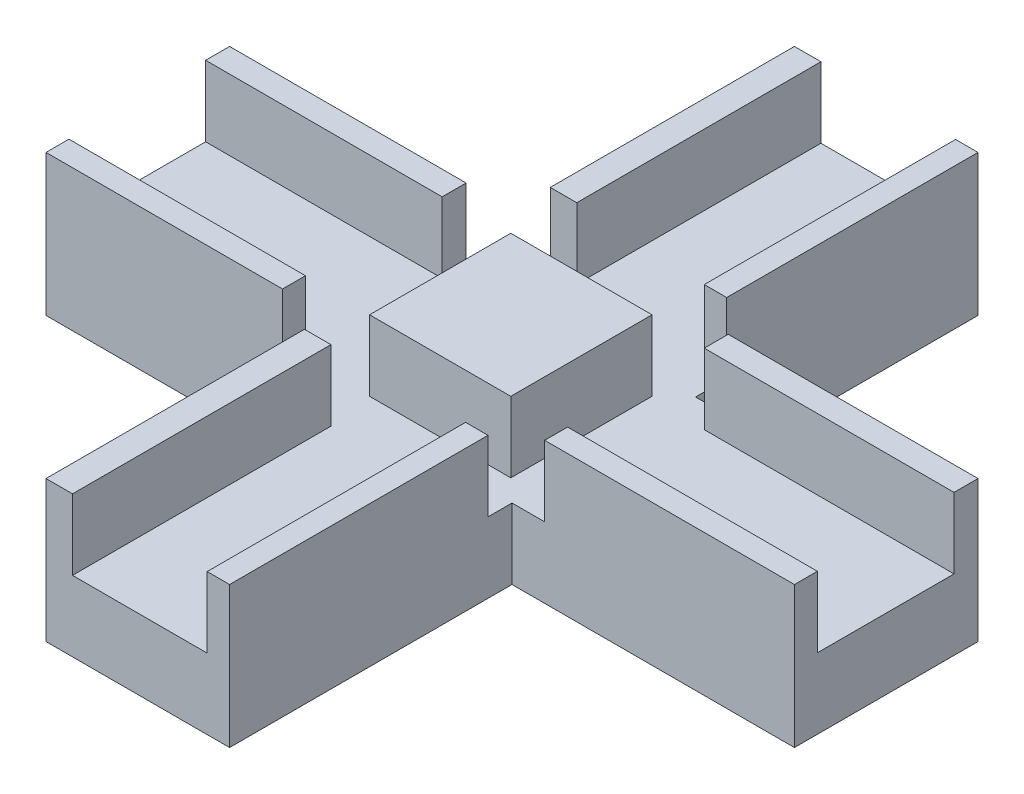
SolidWorks part; units mm, degrees
ref_plane "Front Plane" through (0, 0, 0) normal (0, 0, 1) x (1, 0, 0)
ref_plane "Top Plane" through (0, 0, 0) normal (0, 1, 0) x (1, 0, 0)
ref_plane "Right Plane" through (0, 0, 0) normal (1, 0, 0) x (0, 0, -1)
sketch "Sketch1" plane through (0, 0, 0) normal (0, 1, 0) x (1, 0, 0)
  line L0 (-12.8302, 53) -> (-12.8302, 13)
  line L1 (-12.8302, 13) -> (-52.8302, 13)
  line L2 (-52.8302, 13) -> (-52.8302, -13)
  line L3 (-12.8302, 53) -> (13.1698, 53)
  line L4 (-62.8931, 0) -> (96.6038, 0) construction
  line L5 (0.1698, 63.0629) -> (0.1698, -67) construction
  line L6 (-12.8302, -53) -> (13.1698, -53)
  line L7 (-12.8302, -13) -> (-52.8302, -13)
  line L8 (-12.8302, -53) -> (-12.8302, -13)
  line L9 (13.1698, -53) -> (13.1698, -13)
  line L10 (13.1698, -13) -> (53.1698, -13)
  line L11 (53.1698, 13) -> (53.1698, -13)
  line L12 (13.1698, 13) -> (53.1698, 13)
  line L13 (13.1698, 53) -> (13.1698, 13)
  point P13 (-52.8302, 0)
  point P14 (53.1698, 0)
  point P18 (0.1698, -53)
  point P19 (0.1698, 53)
  dimension "D1" = 40
  dimension "D2" = 13
extrude "Boss-Extrude1" add sketch "Sketch1" against normal blind 10
sketch "Sketch3" plane through (0, 0, 0) normal (0, 1, 0) x (1, 0, 0)
  line L0 (-10, 10) -> (-10, -10)
  line L1 (-10, -10) -> (10, -10)
  line L2 (10, -10) -> (10, 10)
  line L3 (10, 10) -> (-10, 10)
  dimension "D1" = 10
  dimension "D2" = 10
  dimension "D3" = 10
  dimension "D4" = 10
extrude "Boss-Extrude2" add sketch "Sketch3" along normal blind 10
sketch "Sketch4" plane through (0, 0, 0) normal (0, 1, 0) x (1, 0, 0)
  line L14 (-19.3314, 13) -> (-52.8302, 13)
  line L15 (-12.8302, 13) -> (-52.8302, 13) construction
  line L16 (-52.8302, 13) -> (-52.8302, 9.6061)
  line L17 (-52.8302, 13) -> (-52.8302, -13) construction
  line L18 (-52.8302, 9.6061) -> (-19.3314, 9.6061)
  line L19 (-19.3314, 9.6061) -> (-19.3314, 13)
  line L20 (-19.3314, -9.7506) -> (-52.8302, -9.7506)
  line L21 (-52.8302, -9.7506) -> (-52.8302, -13)
  line L22 (-52.8302, -13) -> (-19.3314, -13)
  line L23 (-52.8302, -13) -> (-12.8302, -13) construction
  line L24 (-19.3314, -13) -> (-19.3314, -9.7506)
  line L25 (-12.8302, -16.3954) -> (-9.0752, -16.3954)
  line L26 (-12.8302, -13) -> (-12.8302, -53) construction
  line L27 (-9.0752, -16.3954) -> (-9.0752, -53)
  line L28 (-12.8302, -53) -> (13.1698, -53) construction
  line L29 (-9.0752, -53) -> (-12.8302, -53)
  line L30 (-12.8302, -53) -> (-12.8302, -16.3954)
  line L31 (9.9926, -16.3954) -> (13.1698, -16.3954)
  line L32 (13.1698, -53) -> (13.1698, -13) construction
  line L33 (13.1698, -16.3954) -> (13.1698, -53)
  line L34 (13.1698, -53) -> (9.9926, -53)
  line L35 (9.9926, -53) -> (9.9926, -16.3954)
  line L36 (17.7931, -13) -> (17.7931, -9.7506)
  line L37 (13.1698, -13) -> (53.1698, -13) construction
  line L38 (17.7931, -9.7506) -> (53.1698, -9.7506)
  line L39 (53.1698, -13) -> (53.1698, 13) construction
  line L40 (53.1698, -9.7506) -> (53.1698, -13)
  line L41 (53.1698, -13) -> (17.7931, -13)
  line L42 (17.7931, 9.6061) -> (17.7931, 13)
  line L43 (53.1698, 13) -> (13.1698, 13) construction
  line L44 (17.7931, 13) -> (53.1698, 13)
  line L45 (53.1698, 13) -> (53.1698, 9.6061)
  line L46 (53.1698, 9.6061) -> (17.7931, 9.6061)
  line L47 (13.1698, 17.4066) -> (13.1698, 53)
  line L48 (13.1698, 13) -> (13.1698, 53) construction
  line L49 (13.1698, 53) -> (9.9926, 53)
  line L50 (13.1698, 53) -> (-12.8302, 53) construction
  line L51 (9.9926, 53) -> (9.9926, 17.4066)
  line L52 (9.9926, 17.4066) -> (13.1698, 17.4066)
  line L53 (-9.0752, 18.4178) -> (-12.8302, 18.4178)
  line L54 (-12.8302, 53) -> (-12.8302, 13) construction
  line L55 (-12.8302, 18.4178) -> (-12.8302, 53)
  line L56 (-12.8302, 53) -> (-9.0752, 53)
  line L57 (-9.0752, 53) -> (-9.0752, 18.4178)
extrude "Boss-Extrude3" add sketch "Sketch4" along normal blind 10
